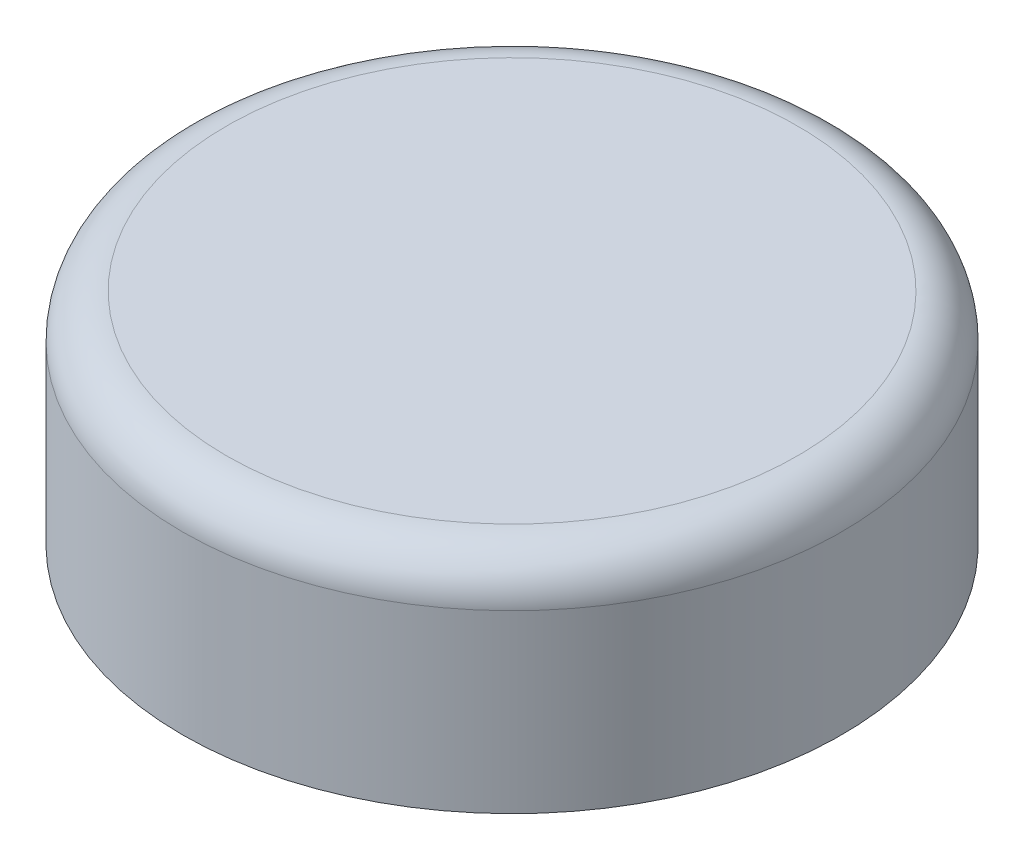
SolidWorks part; units mm, degrees
ref_plane "Front Plane" through (0, 0, 0) normal (0, 0, 1) x (1, 0, 0)
ref_plane "Top Plane" through (0, 0, 0) normal (0, 1, 0) x (1, 0, 0)
ref_plane "Right Plane" through (0, 0, 0) normal (1, 0, 0) x (0, 0, -1)
sketch "Sketch2" plane through (0, 0, 0) normal (1, 0, 0) x (0, 0, -1)
  line L0 (0, 0) -> (-15, 0)
  line L1 (-15, 0) -> (-15, 8)
  line L2 (-13, 10) -> (0, 10)
  line L3 (0, 10) -> (0, 0)
  arc A0 (-15, 8) -> (-13, 10) centre (-13, 8) cw
  dimension "D2" = 2
  dimension "D1" = 15
  dimension "D3" = 10
revolve "Revolve1" add sketch "Sketch2" angle 360 about L3
sketch "Sketch1" plane through (0, 0, 0) normal (0, 1, 0) x (1, 0, 0)
  line L0 (1.55, 2.6847) -> (1.55, -2.6847)
  line L2 (1.55, 0) -> (0, 0) construction
  line L3 (0, 0) -> (3.1, 0) construction
  arc A1 (1.55, 2.6847) -> (1.55, -2.6847) centre (0, 0) ccw
  circle A2 centre (0, 0) radius 3.1 construction
  dimension "D1" = 6.2
extrude "Cut-Extrude2" cut sketch "Sketch1" along normal blind 7.5
